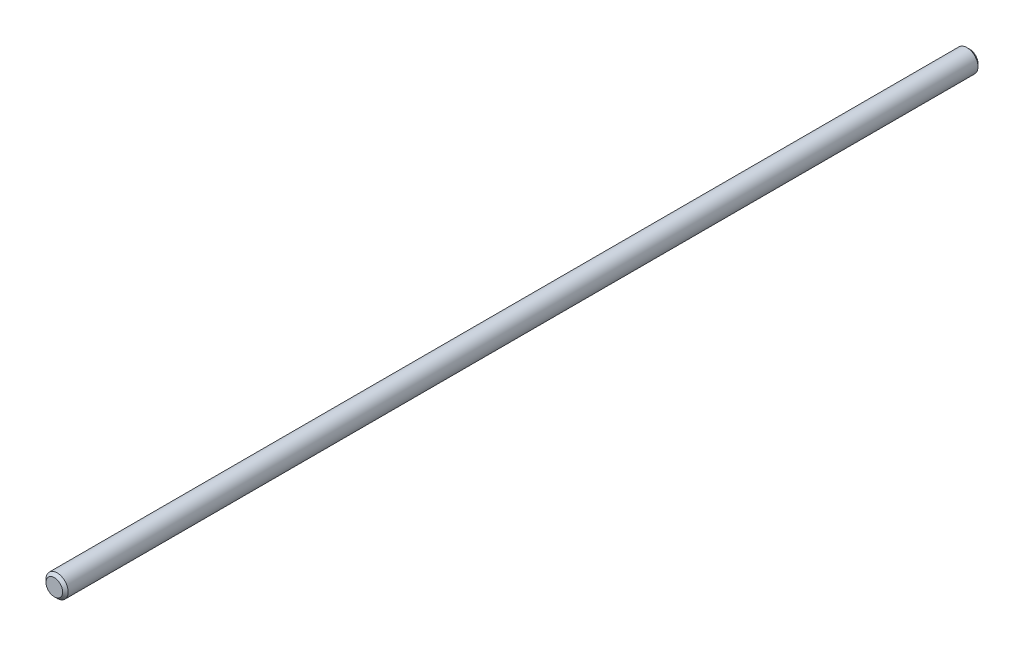
SolidWorks part; units mm, degrees
ref_plane "Piano frontale" through (0, 0, 0) normal (0, 0, 1) x (1, 0, 0)
ref_plane "Piano superiore" through (0, 0, 0) normal (0, 1, 0) x (1, 0, 0)
ref_plane "Piano destro" through (0, 0, 0) normal (1, 0, 0) x (0, 0, -1)
sketch "Schizzo1" plane through (0, 0, 0) normal (0, 0, 1) x (1, 0, 0)
  circle A0 centre (0, 0) radius 4
  dimension "D1" = 8
extrude "Estrusione-Estrusione1" add sketch "Schizzo1" along normal blind 330
chamfer "Smusso1" distance 1 angle 45 2 edges at (4, 0, 330) (4, 0, 0)
